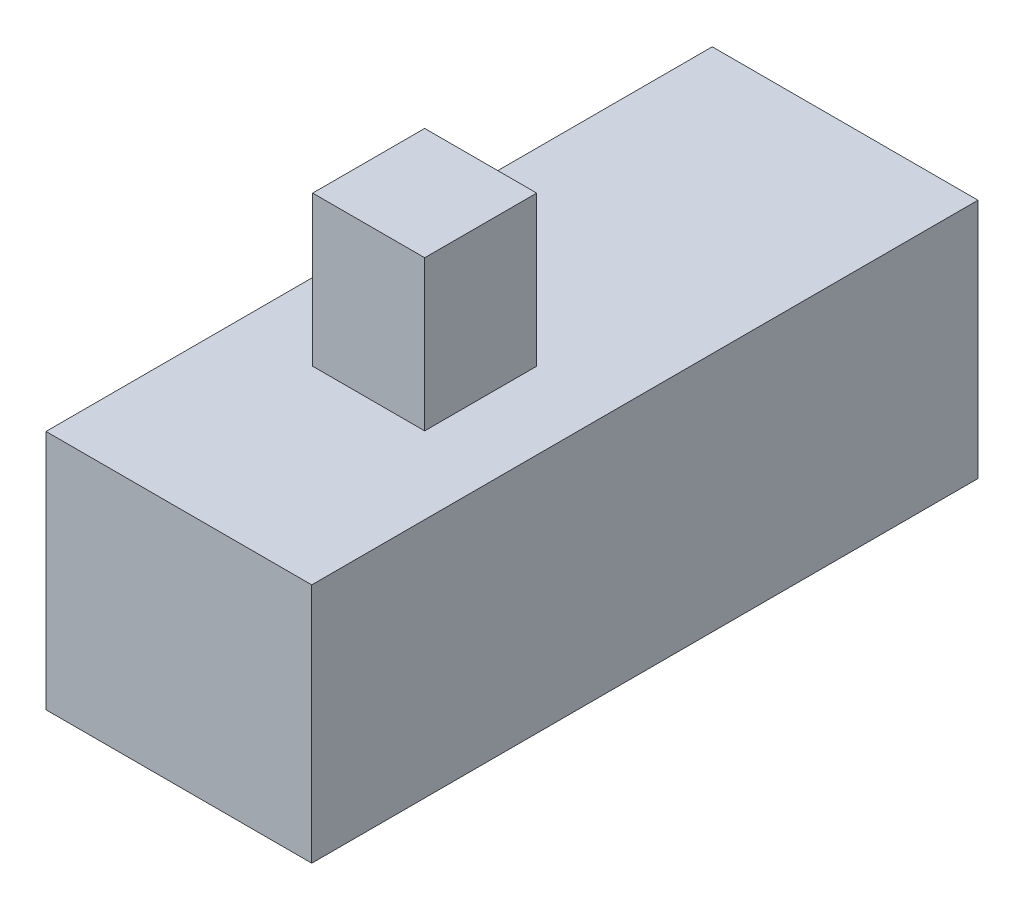
SolidWorks part; units mm, degrees
ref_plane "Front Plane" through (0, 0, 0) normal (0, 0, 1) x (1, 0, 0)
ref_plane "Top Plane" through (0, 0, 0) normal (0, 1, 0) x (1, 0, 0)
ref_plane "Right Plane" through (0, 0, 0) normal (1, 0, 0) x (0, 0, -1)
sketch "Sketch1" plane through (0, 0, 0) normal (0, 1, 0) x (1, 0, 0)
  line L1 (-19.9061, 44.249) -> (-16.3501, 44.249)
  line L2 (-19.9061, 44.249) -> (-19.9061, 35.3336)
  line L3 (-19.9061, 35.3336) -> (-16.3501, 35.3336)
  line L4 (-16.3501, 44.249) -> (-16.3501, 35.3336)
  dimension "D1" = 3.556
  dimension "D2" = 8.9154
extrude "Boss-Extrude1" add sketch "Sketch1" along normal blind 3.2258
sketch "Sketch2" plane through (0, 3.2258, 0) normal (0, 1, 0) x (1, 0, 0)
  line L0 (-19.9061, 35.3336) -> (-16.3501, 35.3336) construction
  line L1 (-18.8774, 39.3722) -> (-17.3788, 39.3722)
  line L2 (-18.8774, 39.3722) -> (-18.8774, 37.8736)
  line L3 (-18.8774, 37.8736) -> (-17.3788, 37.8736)
  line L4 (-17.3788, 39.3722) -> (-17.3788, 37.8736)
  point P4 (-18.1281, 35.3336)
  point P5 (-18.1281, 37.8736)
  dimension "D1" = 1.4986
  dimension "D2" = 1.4986
  dimension "D3" = 2.54
extrude "Boss-Extrude2" add sketch "Sketch2" along normal blind 2.0066
